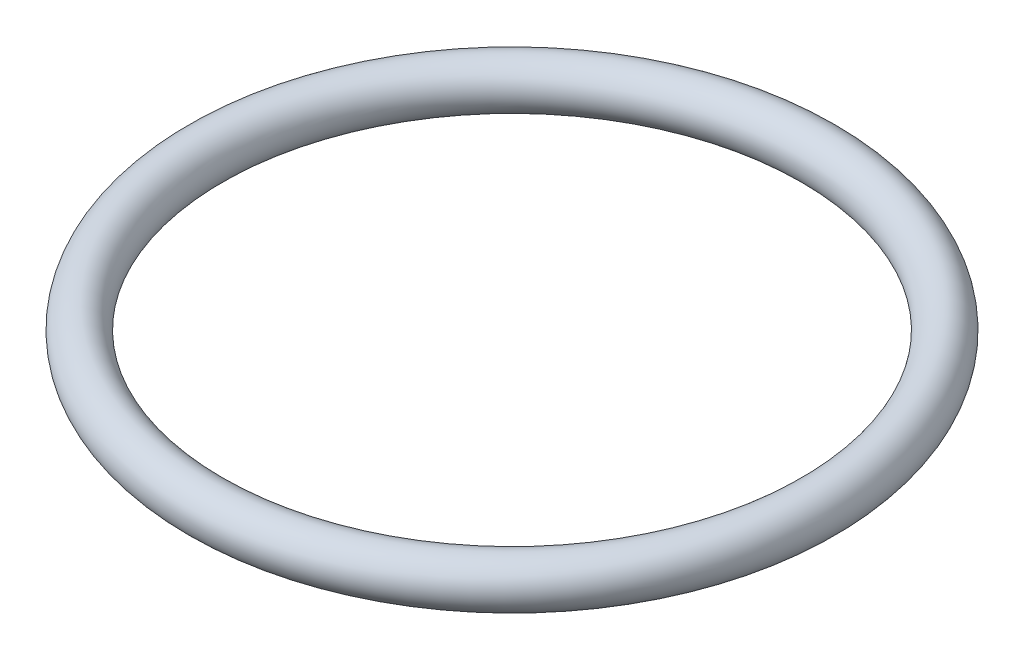
SolidWorks part; units mm, degrees
ref_plane "Front Plane" through (0, 0, 0) normal (0, 0, 1) x (1, 0, 0)
ref_plane "Top Plane" through (0, 0, 0) normal (0, 1, 0) x (1, 0, 0)
ref_plane "Right Plane" through (0, 0, 0) normal (1, 0, 0) x (0, 0, -1)
sketch "Sketch1" plane through (0, 0, 0) normal (0, 0, 1) x (1, 0, 0)
  line L0 (0, 0) -> (0, 2.8331) construction
  circle A0 centre (13, 0) radius 1
  dimension "D1" = 2
  dimension "D2" = 13
revolve "Revolve1" add sketch "Sketch1" angle 360 about L0
